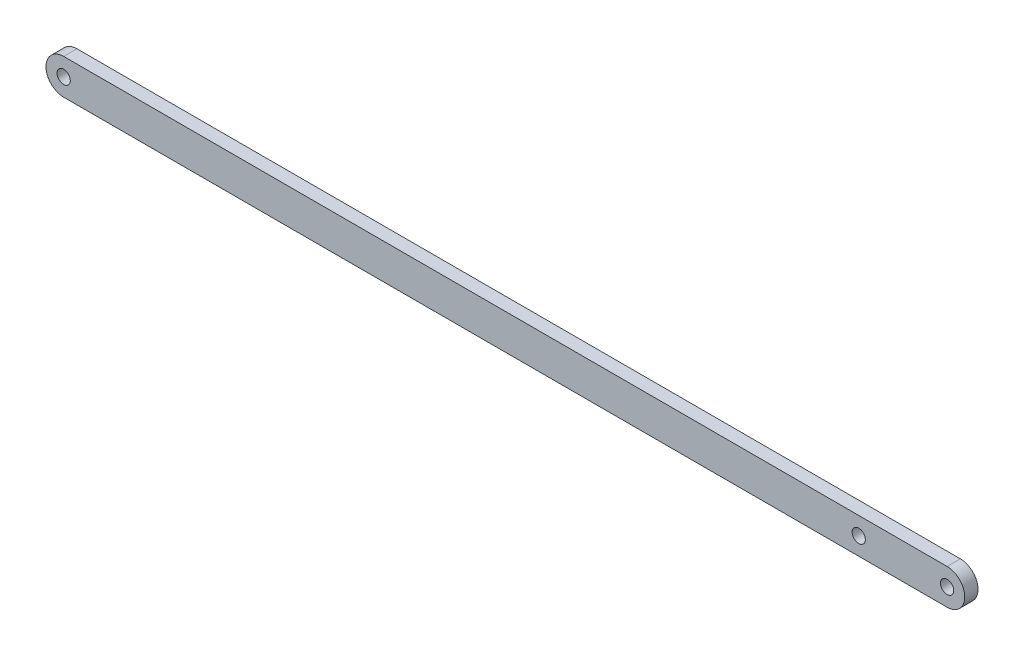
SolidWorks part; units mm, degrees
ref_plane "Front Plane" through (0, 0, 0) normal (0, 0, 1) x (1, 0, 0)
ref_plane "Top Plane" through (0, 0, 0) normal (0, 1, 0) x (1, 0, 0)
ref_plane "Right Plane" through (0, 0, 0) normal (1, 0, 0) x (0, 0, -1)
sketch "Sketch1" plane through (0, 0, 0) normal (0, 0, 1) x (1, 0, 0)
  line L0 (-200, 0) -> (200, 0) construction
  line L1 (-200, 8) -> (200, 8)
  line L2 (-200, -8) -> (200, -8)
  arc A0 (-200, 8) -> (-200, -8) centre (-200, 0) ccw
  arc A1 (200, -8) -> (200, 8) centre (200, 0) ccw
  circle A2 centre (-200, 0) radius 3
  circle A3 centre (200, 0) radius 3
  circle A4 centre (160, 0) radius 3
  point P2 (0, 0)
  dimension "D2" = 8
  dimension "D3" = 6
  dimension "D4" = 8
  dimension "D5" = 6
  dimension "D6" = 360
  dimension "D1" = 400
extrude "Boss-Extrude1" add sketch "Sketch1" against normal blind 6
scale "Scale1" scale about centroid uniform scaling yes scale factor 0.5
